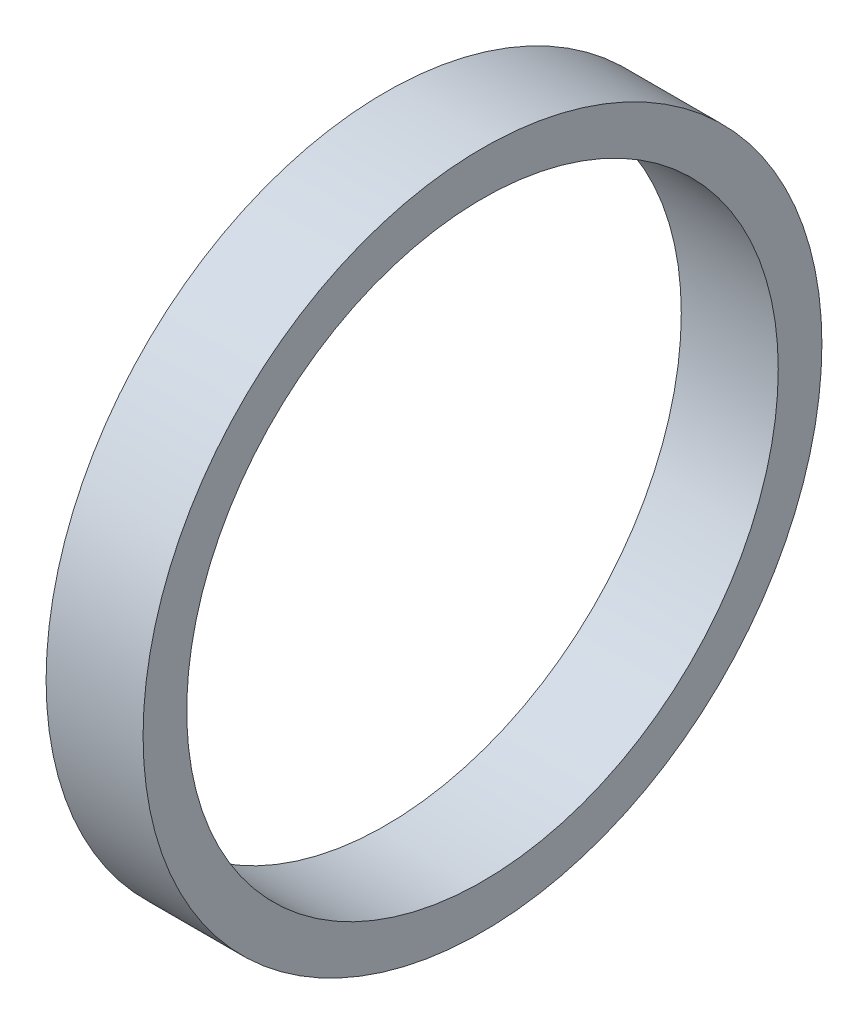
SolidWorks part; units mm, degrees
material "6061-T6 "
ref_plane "Plan de face" through (0, 0, 0) normal (0, 0, 1) x (1, 0, 0)
ref_plane "Plan de dessus" through (0, 0, 0) normal (0, 1, 0) x (1, 0, 0)
ref_plane "Plan de droite" through (0, 0, 0) normal (1, 0, 0) x (0, 0, -1)
sketch "Sketch1" plane through (0, 0, 0) normal (1, 0, 0) x (0, 0, -1)
  circle A0 centre (0, 0) radius 3.05
  circle A1 centre (0, 0) radius 3.5
  dimension "D1" = 6.1
  dimension "D2" = 7
extrude "Boss-Extrude1" add sketch "Sketch1" along normal blind 1
